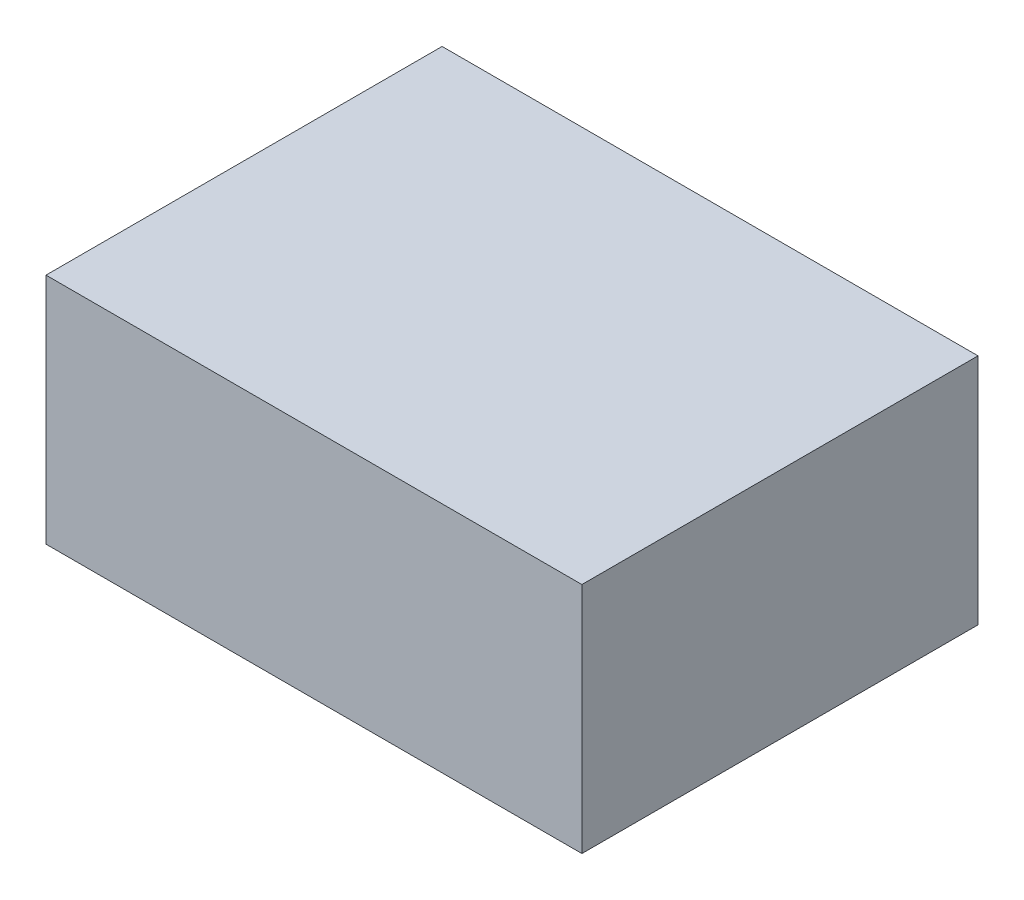
SolidWorks part; units mm, degrees
ref_plane "Front Plane" through (0, 0, 0) normal (0, 0, 1) x (1, 0, 0)
ref_plane "Top Plane" through (0, 0, 0) normal (0, 1, 0) x (1, 0, 0)
ref_plane "Right Plane" through (0, 0, 0) normal (1, 0, 0) x (0, 0, -1)
sketch "Sketch1" plane through (0, 0, 0) normal (0, 1, 0) x (1, 0, 0)
  line L1 (0, 0) -> (230, 0)
  line L2 (0, 0) -> (0, -170)
  line L3 (0, -170) -> (230, -170)
  line L4 (230, 0) -> (230, -170)
  dimension "D1" = 230
  dimension "D2" = 170
extrude "Boss-Extrude1" add sketch "Sketch1" along normal blind 100
